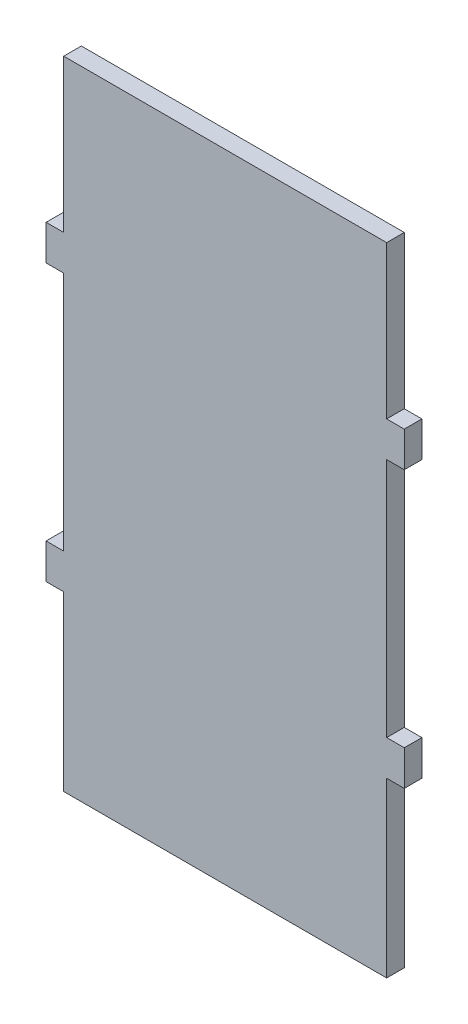
SolidWorks part; units mm, degrees
ref_plane "Přední rovina" through (0, 0, 0) normal (0, 0, 1) x (1, 0, 0)
ref_plane "Horní rovina" through (0, 0, 0) normal (0, 1, 0) x (1, 0, 0)
ref_plane "Pravá rovina" through (0, 0, 0) normal (1, 0, 0) x (0, 0, -1)
sketch "Skica1" plane through (0, 0, 0) normal (0, 0, 1) x (1, 0, 0)
  line L0 (0, 0) -> (55, 0)
  line L1 (0, 0) -> (0, -26)
  line L2 (55, 0) -> (55, -26)
  line L3 (0, -108.46) -> (55, -108.46)
  line L4 (0, -26) -> (-3, -26)
  line L5 (0, -32) -> (-3, -32)
  line L6 (-3, -26) -> (-3, -32)
  line L7 (0, -73) -> (-3, -73)
  line L8 (0, -79) -> (-3, -79)
  line L9 (-3, -73) -> (-3, -79)
  line L10 (55, -79) -> (58, -79)
  line L11 (58, -73) -> (58, -79)
  line L12 (55, -73) -> (58, -73)
  line L13 (55, -26) -> (58, -26)
  line L14 (55, -32) -> (58, -32)
  line L15 (58, -26) -> (58, -32)
  line L16 (55, -79) -> (55, -108.46)
  line L17 (55, -32) -> (55, -73)
  line L18 (0, -32) -> (0, -73)
  line L19 (0, -79) -> (0, -108.46)
  point P20 (0, 0)
  dimension "D1" = 55
  dimension "D2" = 108.46
  dimension "D3" = 3
  dimension "D4" = 3
  dimension "D5" = 6
  dimension "D6" = 6
  dimension "D7" = 26
  dimension "D8" = 41
  dimension "D9" = 6
  dimension "D10" = 26
  dimension "D11" = 3
  dimension "D12" = 6
  dimension "D13" = 41
  dimension "D14" = 3
extrude "Přidat vysunutím1" add sketch "Skica1" along normal blind 3
